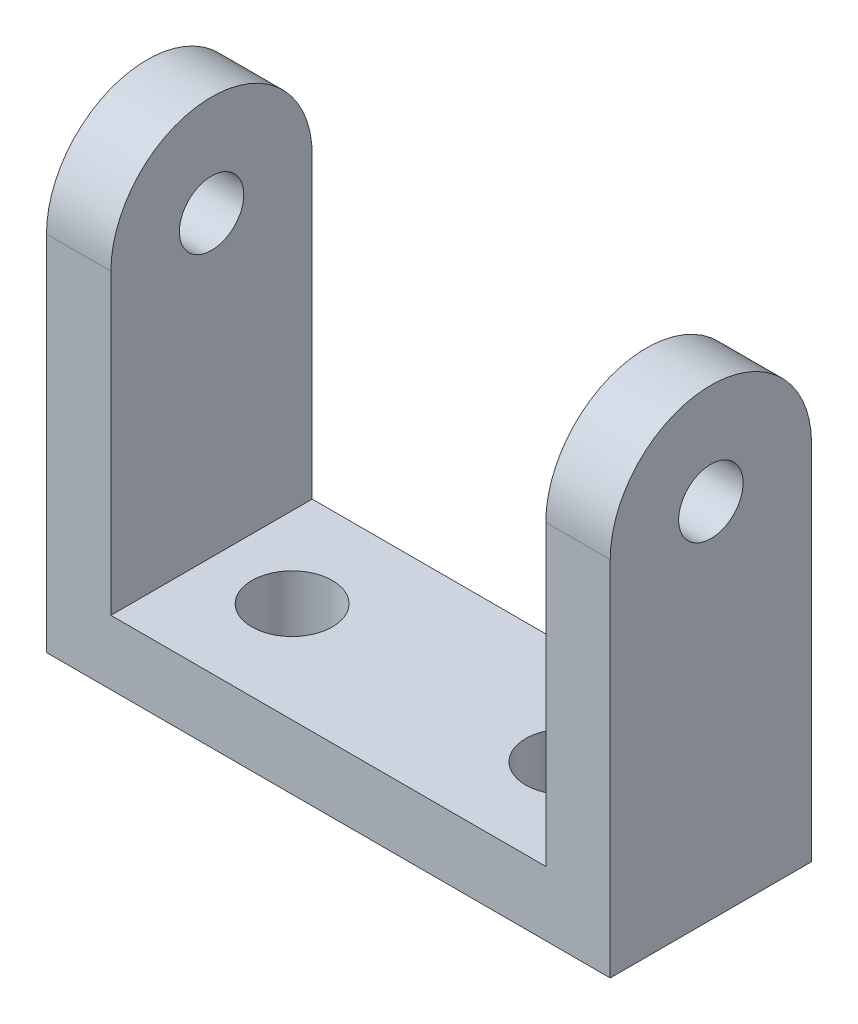
SolidWorks part; units mm, degrees
ref_plane "Front Plane" through (0, 0, 0) normal (0, 0, 1) x (1, 0, 0)
ref_plane "Top Plane" through (0, 0, 0) normal (0, 1, 0) x (1, 0, 0)
ref_plane "Right Plane" through (0, 0, 0) normal (1, 0, 0) x (0, 0, -1)
sketch "Sketch2" plane through (0, 0, 0) normal (0, 0, 1) x (1, 0, 0)
  line L0 (0, 0) -> (35, 0)
  line L1 (35, 0) -> (35, 45)
  dimension "D1" = 35
  dimension "D2" = 45
extrude "Extrude-Thin1" add sketch "Sketch2" against normal blind 25 thin thin type one direction reverse wall 8
sketch "Sketch3" plane through (35, 0, 0) normal (1, 0, 0) x (0, 0, -1)
  line L0 (25, 45) -> (0, 45) construction
  line L1 (25, 45) -> (0, 45)
  arc A0 (0, 45) -> (25, 45) centre (12.5, 45) cw
extrude "Boss-Extrude1" add sketch "Sketch3" against normal up to surface (8 mm away) up to face at (27, 26.5, -12.5)
sketch "Sketch5" plane through (35, 0, 0) normal (1, 0, 0) x (0, 0, -1)
  line L0 (25, 45) -> (0, 45)
  line L1 (12.5, 57.5) -> (12.5, 45)
  arc A0 (25, 45) -> (0, 45) centre (12.5, 45) ccw construction
  point P10 (12.5, 45)
hole_wizard "Ø8.0 (8) Diameter Hole1" positions "3DSketch2" profile "Sketch6" hole size "Ø8.0" standard "ISO" end condition through all
sketch3d "3DSketch2"
  point P0 (35, 45, -12.5)
sketch "Sketch6" plane through (35, 45, -12.5) normal (0, 1, 0) x (0, 0, -1)
  line L0 (0, 0) -> (0, 70)
  line L1 (0, 70) -> (4, 70)
  line L2 (4, 70) -> (4, 0)
  line L5 (4, 0) -> (0, 0)
  line L11 (0, -6.35) -> (0, 107.95) construction
  dimension "Thru Hole Dia." = 8
  dimension "Thru Hole Depth" = 70
sketch "Sketch7" plane through (0, 8, 0) normal (0, 1, 0) x (1, 0, 0)
  line L0 (0, 12.5) -> (17, 12.5)
  line L1 (0, 25) -> (0, 0) construction
  point P5 (17, 12.5)
  dimension "D1" = 17
hole_wizard "Ø10.0 (10) Diameter Hole1" positions "3DSketch3" profile "Sketch8" hole size "Ø10.0" standard "ISO" end condition through all
sketch3d "3DSketch3"
  point P0 (17, 8, -12.5)
sketch "Sketch8" plane through (17, 8, -12.5) normal (1, 0, 0) x (0, 0, 1)
  line L0 (0, 0) -> (0, 8)
  line L1 (0, 8) -> (5, 8)
  line L2 (5, 8) -> (5, 0)
  line L5 (5, 0) -> (0, 0)
  line L11 (0, -6.35) -> (0, 107.95) construction
  dimension "Thru Hole Dia." = 10
  dimension "Thru Hole Depth" = 8
mirror "Mirror1" about plane through (0, 0, -25) normal (1, 0, 0) of "Ø10.0 (10) Diameter Hole1", "Ø8.0 (8) Diameter Hole1", "Boss-Extrude1", "Extrude-Thin1"
